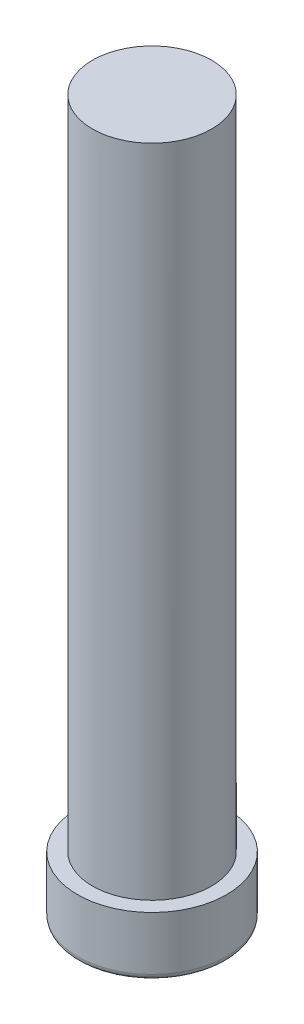
SolidWorks part; units mm, degrees
ref_plane "Front Plane" through (0, 0, 0) normal (0, 0, 1) x (1, 0, 0)
ref_plane "Top Plane" through (0, 0, 0) normal (0, 1, 0) x (1, 0, 0)
ref_plane "Right Plane" through (0, 0, 0) normal (1, 0, 0) x (0, 0, -1)
sketch "Sketch1" plane through (0, 0, 0) normal (0, 1, 0) x (1, 0, 0)
  circle A0 centre (0, 0) radius 25.4
  dimension "D1" = 50.8
extrude "Boss-Extrude1" add sketch "Sketch1" along normal blind 279.4
sketch "Sketch2" plane through (0, 0, 0) normal (0, -1, 0) x (1, 0, 0)
  circle A0 centre (0, 0) radius 31.75
  dimension "D1" = 63.5
extrude "Boss-Extrude2" add sketch "Sketch2" along normal blind 25.4
sketch "Sketch3" plane through (0, -25.4, 0) normal (0, -1, 0) x (1, 0, 0)
  line L0 (25.3038, 0) -> (17.8925, 17.8925)
  line L1 (0, 25.3038) -> (-17.8925, 17.8925)
  line L2 (-17.8925, 17.8925) -> (-25.3038, 0)
  line L3 (-25.3038, 0) -> (-17.8925, -17.8925)
  line L4 (-17.8925, -17.8925) -> (0, -25.3038)
  line L5 (0, -25.3038) -> (17.8925, -17.8925)
  line L6 (17.8925, -17.8925) -> (25.3038, 0)
  line L7 (17.8925, 17.8925) -> (0, 25.3038)
  circle A0 centre (0, 0) radius 23.3777 construction
extrude "Cut-Extrude1" cut sketch "Sketch3" against normal blind 12.7
fillet "Fillet1" radius 2.54 1 edges at (0, -25.4, -31.75)
chamfer "Chamfer1" distance 2.54 angle 74 8 edges at (21.5982, -12.7, 8.9463) (21.5982, -12.7, -8.9463) (8.9463, -12.7, -21.5982) (-8.9463, -12.7, -21.5982) (-21.5982, -12.7, -8.9463) (-21.5982, -12.7, 8.9463) (-8.9463, -12.7, 21.5982) (8.9463, -12.7, 21.5982)
